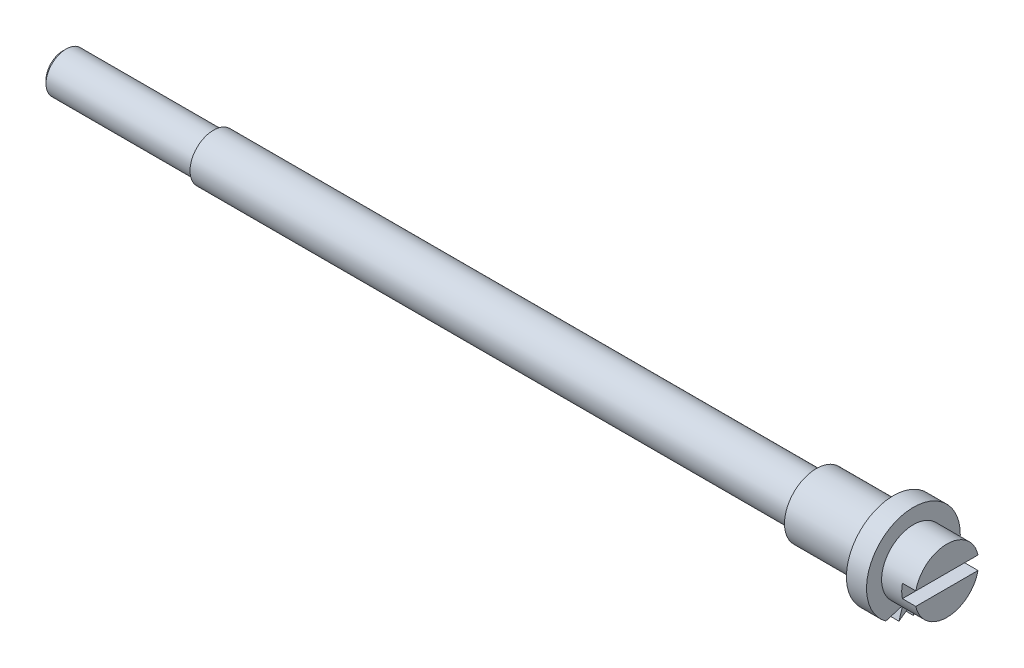
SolidWorks part; units mm, degrees
ref_plane "前视基准面" through (0, 0, 0) normal (0, 0, 1) x (1, 0, 0)
ref_plane "上视基准面" through (0, 0, 0) normal (0, 1, 0) x (1, 0, 0)
ref_plane "右视基准面" through (0, 0, 0) normal (1, 0, 0) x (0, 0, -1)
sketch "草图1" plane through (0, 0, 0) normal (0, 0, 1) x (1, 0, 0)
  line L0 (0, 0) -> (-264, 0) construction
  line L1 (55, 0) -> (-55, 0) construction
  line L2 (-264, 0) -> (-264, 6)
  line L3 (-264, 6) -> (-219, 6)
  line L4 (-219, 6) -> (-219, 7)
  line L5 (-219, 7) -> (-39, 7)
  line L6 (-39, 7) -> (-39, 9.5)
  line L7 (-39, 9.5) -> (-16, 9.5)
  line L8 (-16, 9.5) -> (-16, 14)
  line L9 (-16, 14) -> (-10, 14)
  line L10 (-10, 14) -> (-10, 9.5)
  line L11 (-10, 9.5) -> (0, 9.5)
  line L12 (0, -55) -> (0, 55) construction
  line L13 (0, 9.5) -> (0, 0)
  line L14 (0, 0) -> (-264, 0)
  dimension "D1" = 264
  dimension "D2" = 39
  dimension "D3" = 6
  dimension "D4" = 10
  dimension "D5" = 19
  dimension "D6" = 14
  dimension "D7" = 12
  dimension "D8" = 45
  dimension "D9" = 28
revolve "旋转1" add sketch "草图1" angle 360 about L0
chamfer "倒角1" distance 1 angle 45 1 edges at (-264, 0, -6)
sketch "草图2" plane through (0, 0, 0) normal (1, 0, 0) x (0, 0, -1)
  line L0 (-9.5, 0) -> (9.5, 0)
  circle A0 centre (0, 0) radius 9.5 construction
extrude "切除-拉伸-薄壁1" cut sketch "草图2" against normal blind 4 thin thin type mid plane wall 4
sketch "草图4" plane through (-10, 0, 0) normal (1, 0, 0) x (0, 0, -1)
  line L0 (0, -14) -> (0, -10.3)
  line L1 (0, 15.4) -> (0, -15.4) construction
  line L2 (0, -10.3) -> (-4.3262, -13.3148)
  line L3 (-4.3262, -13.3148) -> (-3.1222, -9.6092) construction
  circle A0 centre (0, 0) radius 10.3 construction
  circle A1 centre (0, 0) radius 14 construction
  point P10 (-3.8923, -13.4481)
  dimension "D1" = 20.6
  dimension "D2" = 18
extrude "切除-拉伸3" cut sketch "草图4" against normal through all and the other way through all
pattern_circular "阵列(圆周)1" count 2 every 18 about axis through (0, 0, 0) along (1, 0, 0) of "切除-拉伸3"
